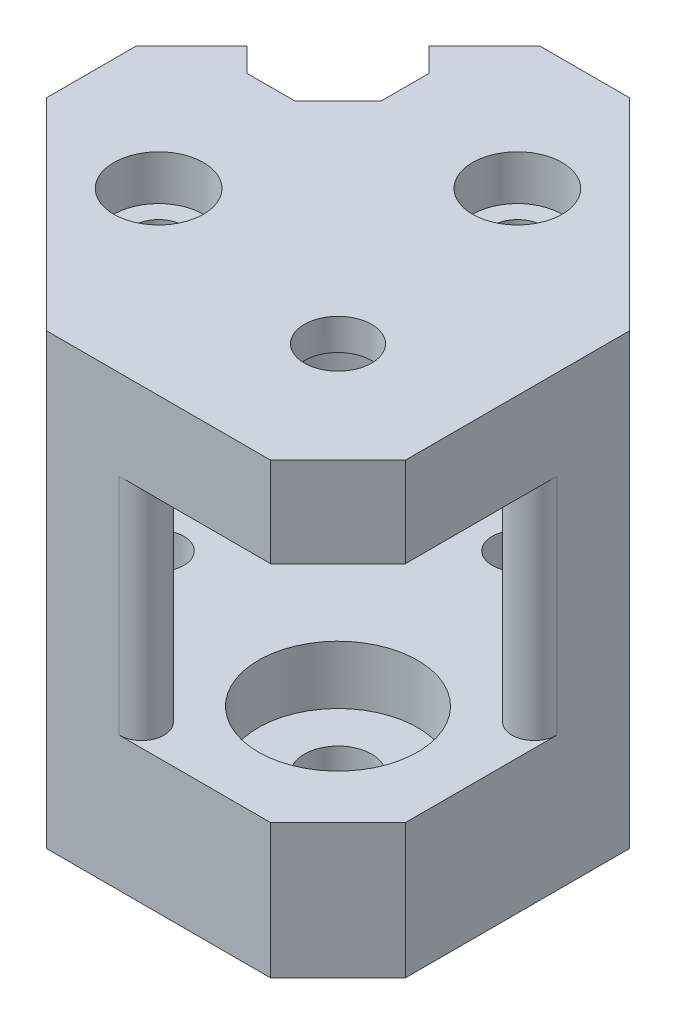
SolidWorks part; units mm, degrees
ref_plane "Front Plane" through (0, 0, 0) normal (0, 0, 1) x (1, 0, 0)
ref_plane "Top Plane" through (0, 0, 0) normal (0, 1, 0) x (1, 0, 0)
ref_plane "Right Plane" through (0, 0, 0) normal (1, 0, 0) x (0, 0, -1)
sketch "Sketch9" plane through (0, 0, 0) normal (0, 1, 0) x (1, 0, 0)
  line L1 (0, 0) -> (36, 0)
  line L2 (0, 0) -> (0, 36)
  line L3 (0, 36) -> (36, 36)
  line L4 (36, 0) -> (36, 36)
  dimension "D1" = 36
  dimension "D2" = 36
extrude "Boss-Extrude1" add sketch "Sketch9" along normal blind 40
chamfer "Chamfer2" distance 18 angle 45 1 edges at (0, 20, -36)
sketch "Sketch10" plane through (36, 0, 0) normal (1, 0, 0) x (0, 0, -1)
  line L4 (0, 0) -> (36, 0)
  line L5 (36, 0) -> (36, 40)
  line L6 (36, 40) -> (0, 40)
  line L7 (0, 40) -> (0, 0)
  line L8 (0, 0) -> (36, 0)
  line L9 (36, 0) -> (36, 40)
  line L10 (36, 40) -> (0, 40)
  line L11 (0, 40) -> (0, 0)
  dimension "D1" = 0
extrude "Boss-Extrude2" add sketch "Sketch10" along normal blind 8
sketch "Sketch12" plane through (0, 0, 0) normal (0, 0, 1) x (1, 0, 0)
  line L4 (0, 0) -> (44, 0)
  line L5 (44, 0) -> (44, 40)
  line L6 (44, 40) -> (0, 40)
  line L7 (0, 40) -> (0, 0)
  line L8 (0, 0) -> (44, 0)
  line L9 (44, 0) -> (44, 40)
  line L10 (44, 40) -> (0, 40)
  line L11 (0, 40) -> (0, 0)
  dimension "D1" = 0
extrude "Boss-Extrude3" add sketch "Sketch12" along normal blind 8
chamfer "Chamfer3" distance 18 angle 45 2 edges at (0, 20, 8) (44, 20, -36)
chamfer "Chamfer4" distance 6 angle 45 1 edges at (44, 20, 8)
sketch "Sketch13" plane through (23, 0, 23) normal (0.7071, 0, 0.7071) x (0.7071, 0, -0.7071)
  line L0 (7.0711, 40) -> (7.0711, 0) construction
  line L1 (7.0711, 32) -> (43.8406, 32)
  line L2 (7.0711, 32) -> (7.0711, 12)
  line L3 (7.0711, 12) -> (43.8406, 12)
  line L4 (43.8406, 32) -> (43.8406, 12)
  line L5 (43.8406, 0) -> (43.8406, 40) construction
  dimension "D1" = 8
  dimension "D2" = 20
extrude "Cut-Extrude6" cut sketch "Sketch13" against normal up to vertex (39.598 mm away)
sketch "Sketch14" plane through (0, 40, 0) normal (0, 1, 0) x (1, 0, 0)
  line L0 (0, 18) -> (0, 10) construction
  circle A0 centre (32, 4) radius 3
  dimension "D2" = 6
  dimension "D1" = 32
  dimension "D3" = 32
extrude "Cut-Extrude7" cut sketch "Sketch14" against normal through all
sketch "Sketch15" plane through (0, 12, 0) normal (0, 1, 0) x (1, 0, 0)
  circle A0 centre (32, 4) radius 7.1
  dimension "D1" = 14.2
extrude "Cut-Extrude8" cut sketch "Sketch15" against normal blind 5.2
sketch "Sketch16" plane through (0, 32, 0) normal (0, -1, 0) x (-1, 0, 0)
  circle A0 centre (-32, 4) radius 7.1
  dimension "D1" = 14.2
extrude "Cut-Extrude9" cut sketch "Sketch16" against normal blind 5.2
sketch "Sketch18" plane through (0, 12, 0) normal (0, 1, 0) x (1, 0, 0)
  line L0 (40.4645, 21.5355) -> (34.8076, 15.8787)
  line L1 (26, 36) -> (44, 18) construction
  line L2 (34.8076, 15.8787) -> (44, 6.6863)
  line L3 (44, -2) -> (44, 18) construction
  line L4 (44, 6.6863) -> (44, 18)
  line L5 (44, 18) -> (40.4645, 21.5355)
  line L6 (14.4645, -4.4645) -> (20.1213, 1.1924)
  line L7 (0, 10) -> (18, -8) construction
  line L8 (20.1213, 1.1924) -> (29.3137, -8)
  line L9 (18, -8) -> (38, -8) construction
  line L10 (29.3137, -8) -> (18, -8)
  line L11 (18, -8) -> (14.4645, -4.4645)
  dimension "D8" = 8
  dimension "D9" = 8
  dimension "D10" = 5
  dimension "D11" = 5
extrude "Boss-Extrude4" add sketch "Sketch18" along normal blind 20
fillet "Fillet1" radius 2 6 edges at (40.4645, 22, -21.5355) (44, 22, -6.6863) (29.3137, 22, 8) (14.4645, 22, 4.4645) (20.1213, 22, -1.1924) (34.8076, 22, -15.8787)
sketch "Sketch19" plane through (0, 40, 0) normal (0, 1, 0) x (1, 0, 0)
  circle A0 centre (12, 8) radius 2.25
  circle A1 centre (28, 24) radius 2.25
  dimension "D5" = 4.5
  dimension "D1" = 2
  dimension "D2" = 12
  dimension "D3" = 2
  dimension "D4" = 12
extrude "Cut-Extrude10" cut sketch "Sketch19" against normal through all
sketch "Sketch20" plane through (0, 0, 0) normal (0, -1, 0) x (-1, 0, 0)
  circle A0 centre (-12, 8) radius 2.8
  circle A1 centre (-28, 24) radius 2.8
  dimension "D1" = 5.6
extrude "Cut-Extrude11" cut sketch "Sketch20" against normal blind 7
sketch "Sketch21" plane through (0, 40, 0) normal (0, 1, 0) x (1, 0, 0)
  circle A0 centre (28, 24) radius 4
  circle A1 centre (12, 8) radius 4
  dimension "D1" = 8
extrude "Cut-Extrude12" cut sketch "Sketch21" against normal blind 4
sketch "Sketch22" plane through (-9, 0, -9) normal (-0.7071, 0, -0.7071) x (-0.7071, 0, 0.7071)
  line L0 (-38.1838, 40) -> (-12.7279, 40) construction
  circle A0 centre (-15.4558, 36) radius 2.1
  circle A1 centre (-35.4558, 36) radius 2.1
  circle A2 centre (-35.4558, 4) radius 2.1
  circle A3 centre (-15.4558, 4) radius 2.1
  point P16 (-25.4558, 40)
  dimension "D5" = 4.2
  dimension "D1" = 4
  dimension "D2" = 20
  dimension "D3" = 10
  dimension "D4" = 32
extrude "Cut-Extrude13" cut sketch "Sketch22" against normal blind 6
sketch "Sketch23" plane through (-9, 0, -9) normal (-0.7071, 0, -0.7071) x (-0.7071, 0, 0.7071)
  line L0 (-38.1838, 40) -> (-12.7279, 40) construction
  line L1 (-31.1838, 40) -> (-19.7279, 40)
  line L2 (-31.1838, 40) -> (-31.1838, 0)
  line L3 (-31.1838, 0) -> (-19.7279, 0)
  line L4 (-19.7279, 40) -> (-19.7279, 0)
  line L5 (-12.7279, 0) -> (-38.1838, 0) construction
  dimension "D1" = 7
  dimension "D2" = 7
extrude "Cut-Extrude14" cut sketch "Sketch23" against normal blind 6
chamfer "Chamfer5" distance 3 angle 45 2 edges at (17.2929, 6, -26.8076) (9.1924, 6, -18.7071)
